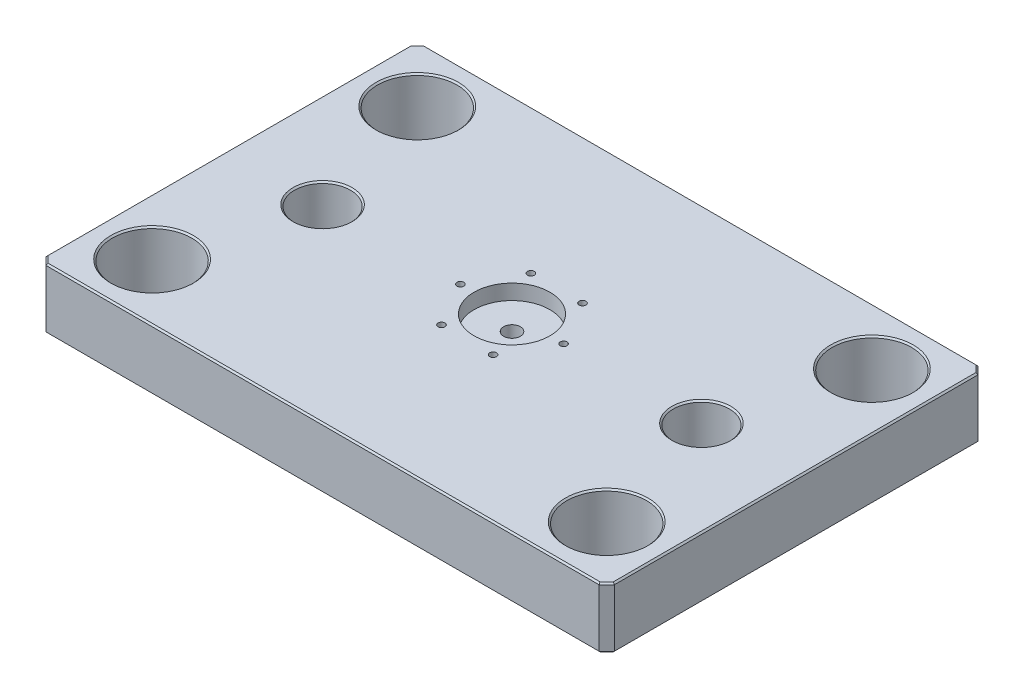
SolidWorks part; units mm, degrees
ref_plane "Płaszczyzna przednia" through (0, 0, 0) normal (0, 0, 1) x (1, 0, 0)
ref_plane "Płaszczyzna górna" through (0, 0, 0) normal (0, 1, 0) x (1, 0, 0)
ref_plane "Płaszczyzna prawa" through (0, 0, 0) normal (1, 0, 0) x (0, 0, -1)
sketch "Szkic1" plane through (0, 0, 0) normal (0, 1, 0) x (1, 0, 0)
  line L1 (-375, -250) -> (375, -250)
  line L2 (-375, -250) -> (-375, 250)
  line L3 (-375, 250) -> (375, 250)
  line L4 (375, -250) -> (375, 250)
  line L5 (-375, -250) -> (375, 250) construction
  line L6 (-375, 250) -> (375, -250) construction
  point P0 (0, 0)
  dimension "D1" = 500
  dimension "D2" = 750
extrude "Wyciągnięcie1" add sketch "Szkic1" along normal blind 80
chamfer "Sfazowanie1" distance 10 angle 45 4 edges at (375, 40, 250) (375, 40, -250) (-375, 40, -250) (-375, 40, 250)
sketch "Szkic2" plane through (0, 80, 0) normal (0, 1, 0) x (1, 0, 0)
  line L0 (0, 218.5392) -> (0, 0) construction
  line L1 (0, 0) -> (-262.0322, 0) construction
  circle A0 centre (-300, 175) radius 52.5
  circle A1 centre (300, 175) radius 52.5
  circle A2 centre (-300, -175) radius 52.5
  circle A3 centre (300, -175) radius 52.5
  dimension "D1" = 105
  dimension "D2" = 350
  dimension "D3" = 600
extrude "Wyciągnięcie2" cut sketch "Szkic2" against normal up to next
sketch "Szkic3" plane through (0, 80, 0) normal (0, 1, 0) x (1, 0, 0)
  line L0 (0, 0) -> (0, 171.0186) construction
  line L1 (-250, 0) -> (0, 0) construction
  circle A0 centre (-250, 0) radius 37
  circle A1 centre (250, 0) radius 37
  dimension "D1" = 74
  dimension "D2" = 500
extrude "Wyciągnięcie3" cut sketch "Szkic3" against normal up to next
chamfer "Sfazowanie2" distance 2 angle 45 28 edges at (-370, 80, 245) (-375, 80, 0) (-370, 80, -245) (0, 80, -250) (370, 80, -245) (375, 80, 0) (370, 80, 245) (0, 80, 250) (-300, 80, -122.5) (300, 80, -227.5) (-300, 80, 122.5) (300, 80, 227.5) (-250, 80, 37) (250, 80, -37) (370, 0, -245) (0, 0, -250) (-370, 0, -245) (-375, 0, 0) (-370, 0, 245) (0, 0, 250) (370, 0, 245) (375, 0, 0) (-300, 0, -227.5) (300, 0, -227.5) (-300, 0, 122.5) (300, 0, 122.5) (-250, 0, -37) (250, 0, -37)
sketch "Szkic4" plane through (0, 0, -250) normal (0, 0, -1) x (-1, 0, 0)
  line L0 (-363.2991, 74.4866) -> (-362.3946, 76.2956)
  line L1 (-362.3946, 76.2956) -> (-361.6258, 76.2956)
  line L2 (-361.6258, 76.2956) -> (-361.6258, 72.2705)
  line L3 (-361.6258, 72.2705) -> (-362.3946, 72.2705)
  line L4 (-362.3946, 72.2705) -> (-362.3946, 74.283)
  line L5 (-362.3946, 74.283) -> (-363.2991, 74.4866)
  line L6 (-358.2791, 76.2956) -> (-359.9524, 73.8082)
  line L7 (-359.9524, 73.8082) -> (-358.2791, 73.8082)
  line L8 (-358.2791, 73.8082) -> (-358.2791, 72.2705)
  line L9 (-358.2791, 72.2705) -> (-357.6667, 72.2705)
  line L10 (-357.6667, 72.2705) -> (-357.6667, 76.2956)
  line L11 (-357.6667, 76.2956) -> (-358.2791, 76.2956)
extrude "Wytnij-wyciągnięcie1" cut sketch "Szkic4" against normal blind 0.1
ref_plane "Płaszczyzna2" through (0, 80, 0) normal (0, -1, 0) x (-1, 0, 0)
sketch "Szkic5" plane through (0, 80, 0) normal (0, -1, 0) x (-1, 0, 0)
  circle A0 centre (0, 0) radius 50
extrude "Wytnij-wyciągnięcie3" cut sketch "Szkic5" along normal blind 20
ref_plane "Płaszczyzna3" through (0, 0, 0) normal (0, -1, 0) x (-1, 0, 0)
sketch "Szkic6" plane through (0, 0, 0) normal (0, -1, 0) x (-1, 0, 0)
  line L0 (411.3277, 0) -> (-414.6382, 0) construction
  line L1 (0, -122.0741) -> (0, 115.4532) construction
  line L3 (-68.1367, 0) -> (-34.0684, -59.0081)
  line L4 (-34.0684, -59.0081) -> (34.0684, -59.0081)
  line L5 (34.0684, -59.0081) -> (68.1367, 0)
  line L6 (68.1367, 0) -> (34.0684, 59.0081)
  line L7 (34.0684, 59.0081) -> (-34.0684, 59.0081)
  line L8 (-34.0684, 59.0081) -> (-68.1367, 0)
  circle A0 centre (0, 0) radius 59.0081 construction
  dimension "D1" = 68.1367
hole_wizard "Pogłębienie walcowe pod M8 Wkręt z łbem walcowym z gniazdem sześciokątnym1" positions "Szkic 3D1" profile "Szkic7" counterbore size "M8" standard "ISO" end condition through all
sketch3d "Szkic 3D1"
  point P0 (-68.1367, 0, 0)
  point P3 (-34.0684, 0, 59.0081)
  point P6 (34.0684, 0, 59.0081)
  point P9 (68.1367, 0, 0)
  point P12 (34.0684, 0, -59.0081)
  point P15 (-34.0684, 0, -59.0081)
sketch "Szkic7" plane through (-68.1367, 0, 0) normal (1, 0, 0) x (0, 0, -1)
  line L0 (0, 0) -> (0, 80)
  line L1 (0, 80) -> (4.5, 80)
  line L3 (4.5, 80) -> (4.5, 8.6)
  line L4 (4.5, 8.6) -> (7.5, 8.6)
  line L5 (7.5, 8.6) -> (7.5, 0)
  line L7 (7.5, 0) -> (0, 0)
  line L11 (0, -6.35) -> (0, 107.95) construction
  dimension "Średnica otworu na wylot" = 9
  dimension "Głębokość otworu na wylot" = 80
  dimension "Średnica pogłębienia walcowego" = 15
  dimension "Głębokość pogłębienia walcowego" = 8.6
hole_wizard "Otwór pod śrubę M201" positions "Szkic10" profile "Szkic11" hole size "M20" standard "ISO" end condition through all
sketch "Szkic10" plane through (0, 0, 0) normal (0, -1, 0) x (-1, 0, 0)
  point P0 (0, 0)
sketch "Szkic11" plane through (0, 0, 0) normal (1, 0, 0) x (0, 0, -1)
  line L0 (0, 0) -> (0, 80)
  line L1 (0, 80) -> (11, 80)
  line L2 (11, 80) -> (11, 0)
  line L5 (11, 0) -> (0, 0)
  line L11 (0, -6.35) -> (0, 107.95) construction
  dimension "Średnica otworu na wylot" = 22
  dimension "Głębokość otworu na wylot" = 80
